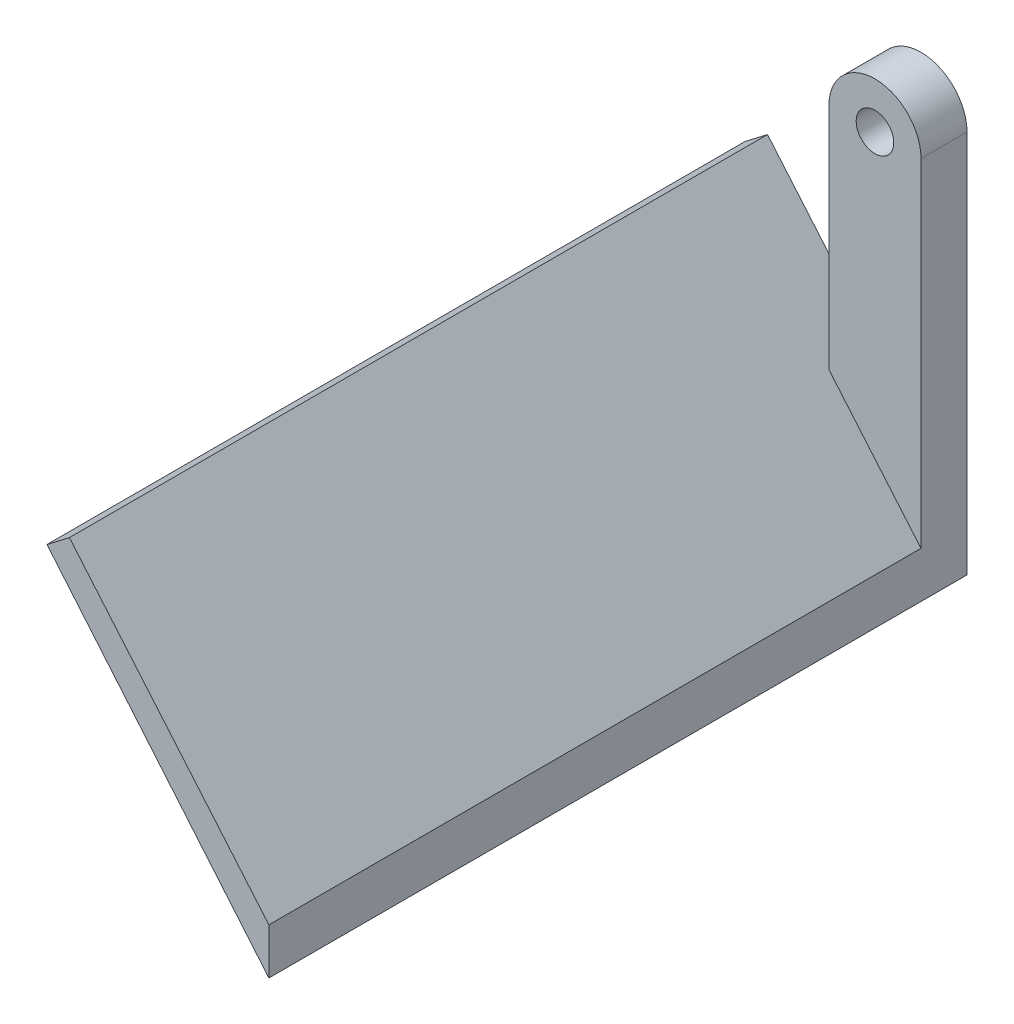
SolidWorks part; units mm, degrees
ref_plane "Alzado" through (0, 0, 0) normal (0, 0, 1) x (1, 0, 0)
ref_plane "Planta" through (0, 0, 0) normal (0, 1, 0) x (1, 0, 0)
ref_plane "Vista lateral" through (0, 0, 0) normal (1, 0, 0) x (0, 0, -1)
sketch "Croquis2" plane through (0, 0, -2903.883) normal (0, 0, -1) x (-1, 0, 0)
  line L2 (-11.1, 0) -> (-11.1, -50)
  line L3 (0.9, 0) -> (0.9, -50)
  line L4 (-11.1, -50) -> (0.9, -50)
  arc A0 (0.9, 0) -> (-11.1, 0) centre (-5.1, 0) ccw
  circle A1 centre (-5.1, 0) radius 2.45
  dimension "D1" = 12
  dimension "D2" = 6
  dimension "D3" = 12
  dimension "D4" = 50
extrude "Saliente-Extruir1" add sketch "Croquis2" along normal blind 6 contours L2 L4 L3 A0 | A1
sketch "Croquis3" plane through (0, 0, -2909.883) normal (0, 0, -1) x (-1, 0, 0)
  line L0 (-11.1, -50) -> (17.8254, -15.528)
  line L1 (17.8254, -15.528) -> (14.9036, -13.2874)
  line L2 (-11.1, 0) -> (-11.1, -50) construction
  line L3 (-11.1, -44) -> (-11.1, -50)
  line L4 (-11.1, -44) -> (14.9036, -13.2874)
  point P3 (0, 0)
  point P4 (17.8254, -46.8129)
  point P5 (15.0202, -47.9838)
  point P6 (14.7375, -47.9578)
  point P9 (14.165, -47.5842)
  point P10 (-11.1, -79)
  point P13 (-11.1, -79)
  point P14 (17.8254, -50.528)
  point P15 (0, 0)
  point P16 (11.6953, -51.1436)
  point P17 (0, 0)
  point P18 (17.8254, -15.528)
  point P19 (14.9036, -13.2874)
  dimension "D1" = 6
  dimension "D2" = 45
  dimension "D3" = 140
extrude "Saliente-Extruir2" add sketch "Croquis3" against normal blind 91 contours L0 L1 L4 L3
sketch "Croquis4" plane through (0, 0, -2909.883) normal (0, 0, -1) x (-1, 0, 0)
  line L0 (0.9, -35.699) -> (-11.1, -50)
  line L1 (0.9, -35.699) -> (-12.6152, -51.8057)
  line L2 (0.9, -35.699) -> (17.8254, -15.528) construction
  line L3 (-12.6152, -51.8057) -> (4.8444, -87.2008)
  line L4 (4.8444, -87.2008) -> (-9.7482, -87.2008)
  line L5 (-9.7482, -87.2008) -> (-11.1, -50)
  point P4 (-9.7482, -87.2008)
  point P10 (4.8444, -87.2008)
extrude "Cortar-Extruir1" cut sketch "Croquis4" against normal blind 91
